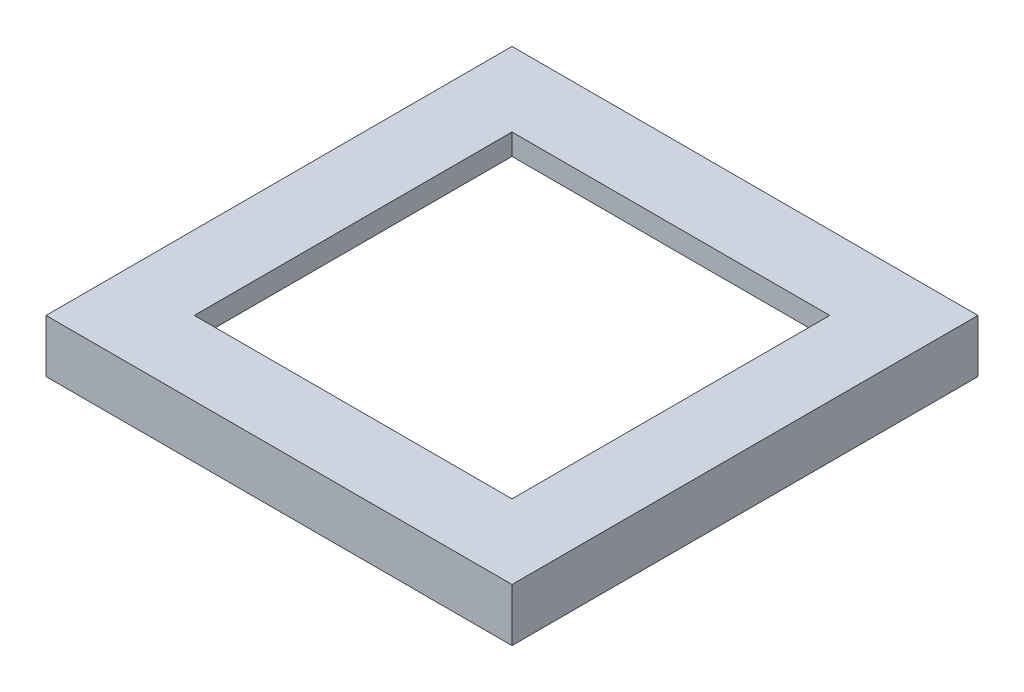
SolidWorks part; units mm, degrees
ref_plane "Front Plane" through (0, 0, 0) normal (0, 0, 1) x (1, 0, 0)
ref_plane "Top Plane" through (0, 0, 0) normal (0, 1, 0) x (1, 0, 0)
ref_plane "Right Plane" through (0, 0, 0) normal (1, 0, 0) x (0, 0, -1)
sketch "Sketch1" plane through (0, 0, 0) normal (0, 1, 0) x (1, 0, 0)
  line L1 (-22, -22) -> (22, -22)
  line L2 (-22, -22) -> (-22, 22)
  line L3 (-22, 22) -> (22, 22)
  line L4 (22, -22) -> (22, 22)
  line L5 (-22, -22) -> (22, 22) construction
  line L6 (-22, 22) -> (22, -22) construction
  point P0 (0, 0)
extrude "Boss-Extrude1" add sketch "Sketch1" along normal blind 5 contours L3 L4 L1 L2
sketch "Sketch3" plane through (0, 5, 0) normal (0, 1, 0) x (1, 0, 0)
  line L1 (-15, -15) -> (15, -15)
  line L2 (-15, -15) -> (-15, 15)
  line L3 (-15, 15) -> (15, 15)
  line L4 (15, -15) -> (15, 15)
  line L5 (-15, -15) -> (15, 15) construction
  line L6 (-15, 15) -> (15, -15) construction
  point P0 (0, 0)
extrude "Cut-Extrude1" cut sketch "Sketch3" against normal blind 2
sketch "Sketch5" plane through (0, 0, 0) normal (0, -1, 0) x (1, 0, 0)
  line L1 (-19.5, -19.5) -> (19.5, -19.5)
  line L2 (-19.5, -19.5) -> (-19.5, 19.5)
  line L3 (-19.5, 19.5) -> (19.5, 19.5)
  line L4 (19.5, -19.5) -> (19.5, 19.5)
  line L5 (-19.5, -19.5) -> (19.5, 19.5) construction
  line L6 (-19.5, 19.5) -> (19.5, -19.5) construction
  point P0 (0, 0)
extrude "Cut-Extrude3" cut sketch "Sketch5" against normal blind 3
